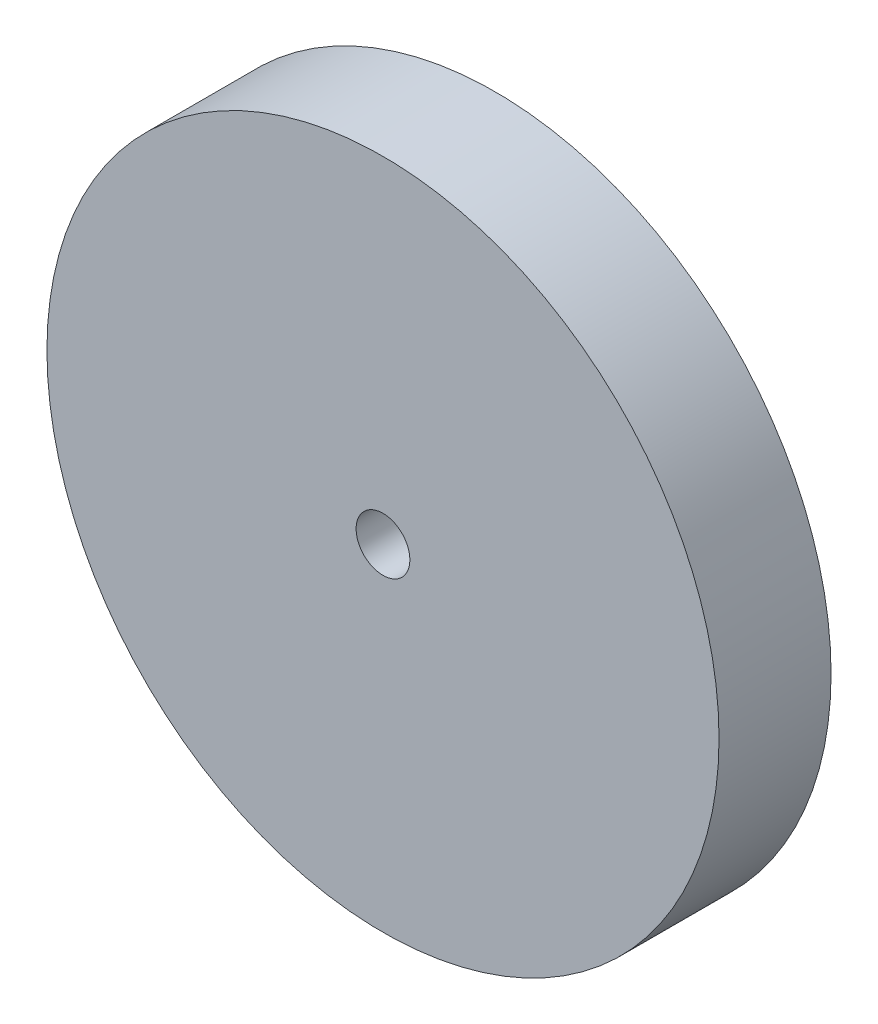
SolidWorks part; units mm, degrees
ref_plane "Front Plane" through (0, 0, 0) normal (0, 0, 1) x (1, 0, 0)
ref_plane "Top Plane" through (0, 0, 0) normal (0, 1, 0) x (1, 0, 0)
ref_plane "Right Plane" through (0, 0, 0) normal (1, 0, 0) x (0, 0, -1)
sketch "Sketch1" plane through (0, 0, 0) normal (0, 0, 1) x (1, 0, 0)
  circle A0 centre (0, 0) radius 15
  circle A1 centre (0, 0) radius 1.2
  dimension "D1" = 2.4
  dimension "D2" = 30
extrude "Boss-Extrude1" add sketch "Sketch1" along normal blind 5
